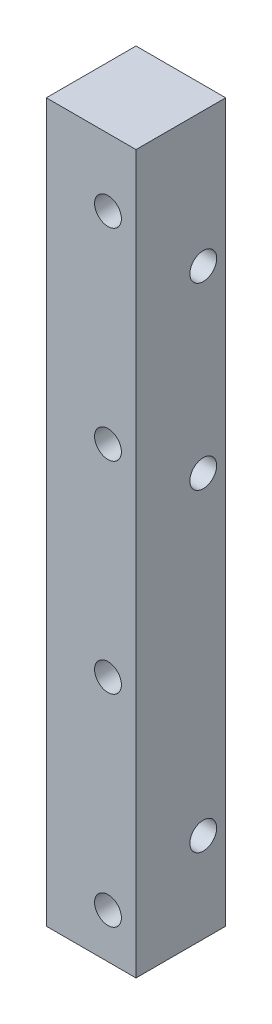
SolidWorks part; units mm, degrees
material "6061 Alloy"
ref_plane "Front" through (0, 0, 0) normal (0, 0, 1) x (1, 0, 0)
ref_plane "Top" through (0, 0, 0) normal (0, 1, 0) x (1, 0, 0)
ref_plane "Right" through (0, 0, 0) normal (1, 0, 0) x (0, 0, -1)
sketch "Sketch1" plane through (0, 0, 0) normal (0, 1, 0) x (1, 0, 0)
  line L1 (-6.35, 6.35) -> (6.35, 6.35)
  line L2 (-6.35, 6.35) -> (-6.35, -6.35)
  line L3 (-6.35, -6.35) -> (6.35, -6.35)
  line L4 (6.35, 6.35) -> (6.35, -6.35)
  line L5 (-6.35, 6.35) -> (6.35, -6.35) construction
  line L6 (-6.35, -6.35) -> (6.35, 6.35) construction
  point P0 (0, 0)
  dimension "D1" = 12.7
extrude "Boss-Extrude1" add sketch "Sketch1" along normal blind 101.6
hole_wizard "Tap Drill for #10-24 Tap1" positions "Sketch2" profile "Sketch3" hole size "#10-24" standard "ANSI Inch" end condition through all
sketch "Sketch2" plane through (6.35, 0, 0) normal (1, 0, 0) x (0, 0, -1)
  line L0 (-9.525, 101.1752) -> (-9.525, 0) construction
  line L1 (-6.35, 101.6) -> (-6.35, 0) construction
  line L2 (-6.35, 0) -> (6.35, 0) construction
  line L3 (-6.35, 101.6) -> (6.35, 101.6) construction
  point P6 (3.175, 12.7)
  point P8 (3.175, 57.15)
  point P10 (3.175, 82.55)
  dimension "D1" = 3.175
  dimension "D2" = 12.7
  dimension "D3" = 12.7
  dimension "D4" = 25.4
  dimension "D5" = 19.05
sketch "Sketch3" plane through (6.35, 82.55, -3.175) normal (0, 1, 0) x (0, 0, -1)
  line L0 (0, 0) -> (0, 12.7)
  line L1 (0, 12.7) -> (1.8986, 12.7)
  line L2 (1.8986, 12.7) -> (1.8986, 0)
  line L5 (1.8986, 0) -> (0, 0)
  line L11 (0, -6.35) -> (0, 107.95) construction
  dimension "Thru Hole Dia." = 3.7973
  dimension "Thru Hole Depth" = 12.7
hole_wizard "Tap Drill for #10-24 Tap2" positions "Sketch4" profile "Sketch5" hole size "#10-24" standard "ANSI Inch" end condition through all
sketch "Sketch4" plane through (0, 0, 6.35) normal (0, 0, 1) x (1, 0, 0)
  line L0 (2.3813, 0) -> (2.3813, 101.6) construction
  line L1 (-6.35, 0) -> (6.35, 0) construction
  line L2 (-6.35, 101.6) -> (6.35, 101.6) construction
  line L4 (6.35, 101.6) -> (6.35, 0) construction
  point P11 (2.3813, 6.35)
  point P13 (2.3813, 34.925)
  point P17 (2.3813, 63.5)
  point P19 (2.3813, 92.075)
  dimension "D1" = 3.9688
  dimension "D2" = 6.35
  dimension "D3" = 28.575
  dimension "D4" = 28.575
  dimension "D5" = 28.575
sketch "Sketch5" plane through (2.3813, 92.075, 6.35) normal (1, 0, 0) x (0, -1, 0)
  line L0 (0, 0) -> (0, 12.7)
  line L1 (0, 12.7) -> (1.8986, 12.7)
  line L2 (1.8986, 12.7) -> (1.8986, 0)
  line L5 (1.8986, 0) -> (0, 0)
  line L11 (0, -6.35) -> (0, 107.95) construction
  dimension "Thru Hole Dia." = 3.7973
  dimension "Thru Hole Depth" = 12.7
